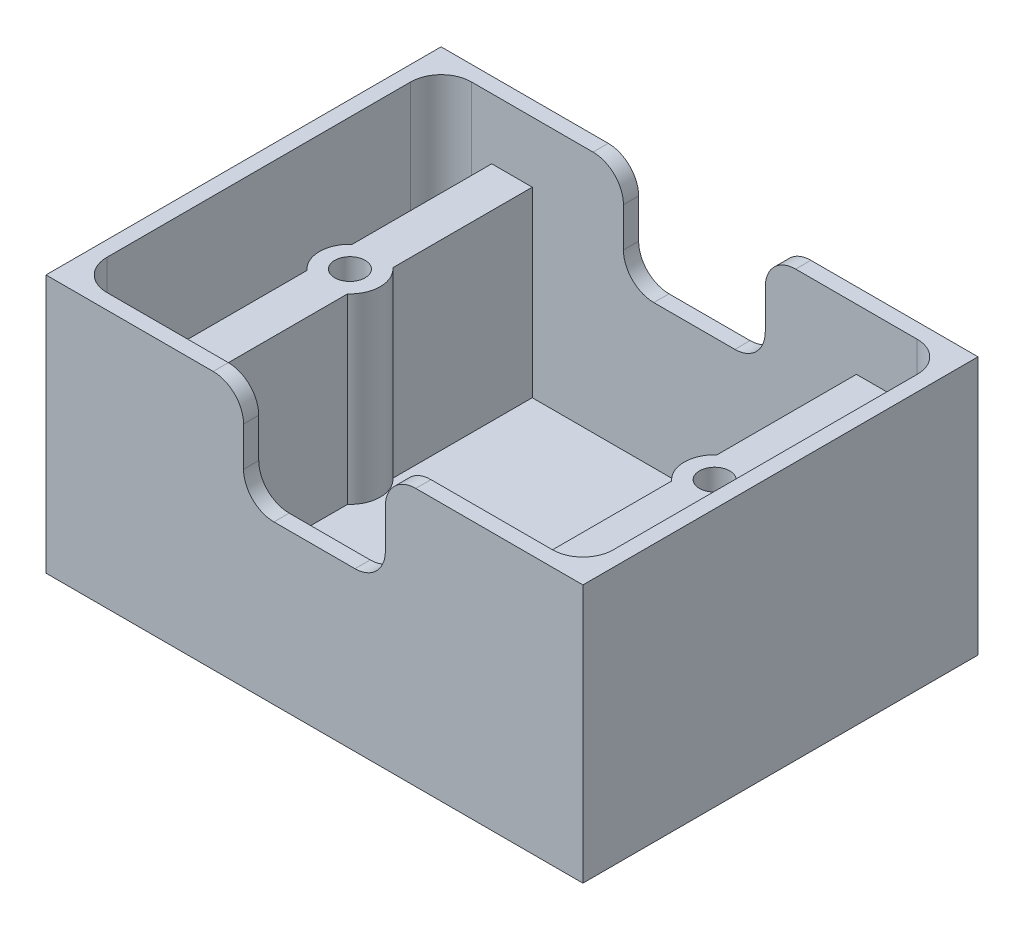
SolidWorks part; units mm, degrees
ref_plane "Front Plane" through (0, 0, 0) normal (0, 0, 1) x (1, 0, 0)
ref_plane "Top Plane" through (0, 0, 0) normal (0, 1, 0) x (1, 0, 0)
ref_plane "Right Plane" through (0, 0, 0) normal (1, 0, 0) x (0, 0, -1)
sketch "Sketch1" plane through (0, 0, 0) normal (0, 1, 0) x (1, 0, 0)
  line L1 (0, 0) -> (50, 0)
  line L2 (0, 0) -> (0, -36)
  line L3 (0, -36) -> (50, -36)
  line L4 (50, 0) -> (50, -36)
  dimension "D1" = 50
  dimension "D2" = 36
extrude "Boss-Extrude1" add sketch "Sketch1" along normal blind 24
shell "Shell1" thickness 1.5
sketch "Sketch2" plane through (0, 0, 0) normal (0, 1, 0) x (1, 0, 0)
  line L0 (50, 0) -> (0, 0) construction
  line L1 (5, 0) -> (9, 0)
  line L2 (5, 0) -> (5, -36)
  line L3 (5, -36) -> (9, -36)
  line L4 (9, 0) -> (9, -36)
  line L5 (0, -36) -> (50, -36) construction
  line L6 (25, 0) -> (25, -71.172) construction
  line L7 (45, -36) -> (41, -36)
  line L8 (41, 0) -> (41, -36)
  line L9 (45, 0) -> (41, 0)
  line L10 (45, 0) -> (45, -36)
  dimension "D1" = 4
  dimension "D2" = 16
extrude "Boss-Extrude2" add sketch "Sketch2" along normal blind 18
sketch "Sketch3" plane through (0, 0, 0) normal (0, 1, 0) x (1, 0, 0)
  line L0 (-7.5821, -25) -> (66.7821, -25) construction
sketch "Sketch4" plane through (0, 18, 0) normal (0, 1, 0) x (1, 0, 0)
  line L0 (25, -36) -> (25, -57.4435) construction
  line L2 (0, -36) -> (50, -36) construction
  circle A0 centre (7, -16) radius 3
  circle A2 centre (43, -16) radius 3
  point P4 (12, -19.5919)
  point P5 (12, -17.3235)
  point P10 (12, -25)
  dimension "D1" = 6
  dimension "D2" = 18
  dimension "D3" = 20
sketch "Sketch6" plane through (0, 0, 37.5) normal (0, 0, 1) x (1, 0, 0)
  line L0 (25, 24) -> (25, -9.6606) construction
  line L1 (18, 14.1347) -> (32, 14.1347)
  line L2 (18, 14.1347) -> (18, 28.1347)
  line L3 (18, 28.1347) -> (32, 28.1347)
  line L4 (32, 14.1347) -> (32, 28.1347)
  line L5 (-1.5, 24) -> (51.5, 24) construction
  dimension "D1" = 14
  dimension "D2" = 7
  dimension "D3" = 14
extrude "Cut-Extrude2" cut sketch "Sketch6" against normal blind 58
fillet "Fillet1" radius 3 12 edges at (50, 12, 36) (0, 12, 36) (50, 12, 0) (0, 12, 0) (18, 24, -0.75) (18, 14.1347, -0.75) (32, 14.1347, -0.75) (32, 24, -0.75) (18, 24, 36.75) (18, 14.1347, 36.75) (32, 14.1347, 36.75) (32, 24, 36.75)
extrude "Boss-Extrude3" add sketch "Sketch4" against normal up to surface (18 mm away) up to face at (25, 0, 18)
sketch "Sketch7" plane through (0, 18, 0) normal (0, 1, 0) x (1, 0, 0)
  line L0 (25, -36) -> (25, -57.6999) construction
  line L1 (29, -36) -> (21, -36) construction
  line L2 (5, -36) -> (9, -36) construction
  circle A0 centre (7, -16) radius 1.5
  circle A1 centre (43, -16) radius 1.5
  dimension "D1" = 18
  dimension "D2" = 20
extrude "Cut-Extrude3" cut sketch "Sketch7" against normal blind 5
